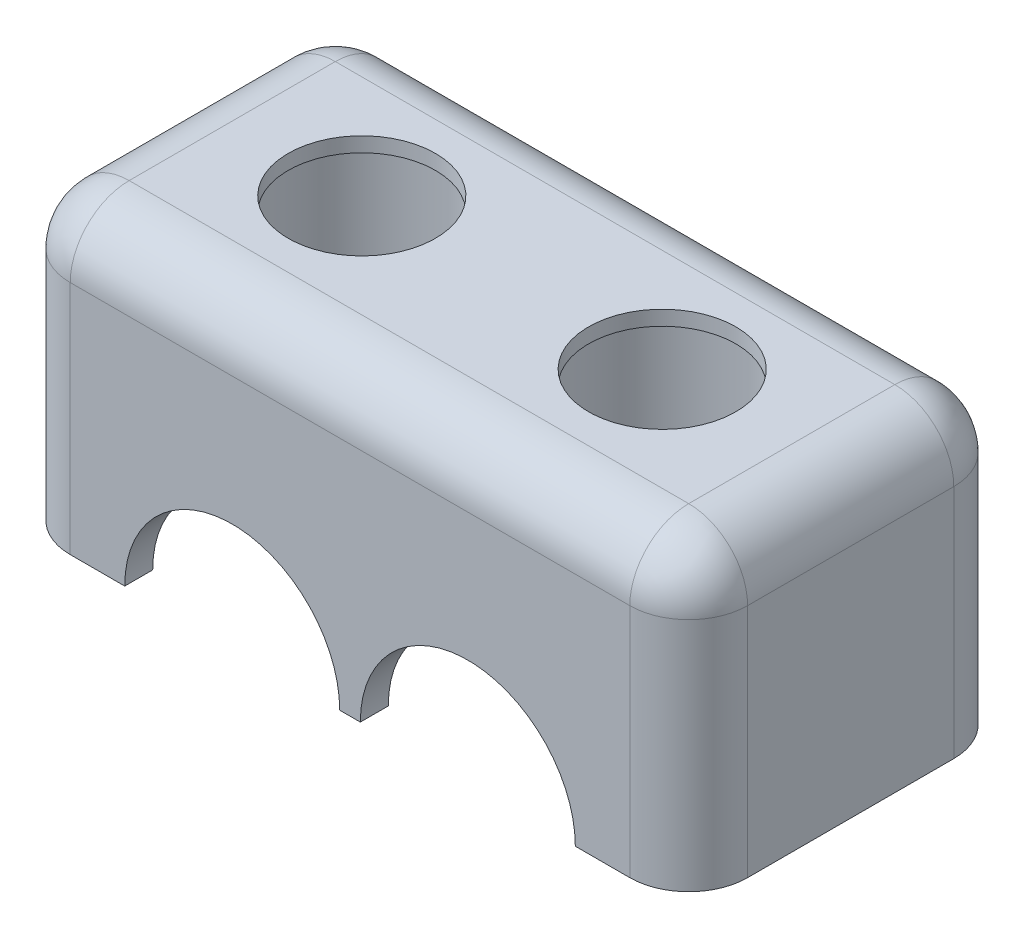
SolidWorks part; units mm, degrees
ref_plane "Front Plane" through (0, 0, 0) normal (0, 0, 1) x (1, 0, 0)
ref_plane "Top Plane" through (0, 0, 0) normal (0, 1, 0) x (1, 0, 0)
ref_plane "Right Plane" through (0, 0, 0) normal (1, 0, 0) x (0, 0, -1)
sketch "Sketch2" plane through (0, 0, 0) normal (0, 0, 1) x (1, 0, 0)
  line L1 (29.21, -5.08) -> (29.21, -25.4)
  line L2 (29.21, -25.4) -> (19.431, -25.4)
  line L3 (0.889, -25.4) -> (-0.889, -25.4)
  line L4 (-19.431, -25.4) -> (-29.21, -25.4)
  line L5 (-29.21, -25.4) -> (-29.21, -5.08)
  line L6 (-24.13, 0) -> (24.13, 0)
  arc A0 (19.431, -25.4) -> (0.889, -25.4) centre (10.16, -25.4) ccw
  arc A1 (-0.889, -25.4) -> (-19.431, -25.4) centre (-10.16, -25.4) ccw
  arc A2 (24.13, 0) -> (29.21, -5.08) centre (24.13, -5.08) cw
  arc A3 (-29.21, -5.08) -> (-24.13, 0) centre (-24.13, -5.08) cw
  point P0 (0, 0)
  point P17 (-29.21, 0)
  dimension "D1" = 18.542
  dimension "D3" = 5.08
  dimension "D2" = 25.4
  dimension "D4" = 19.05
  dimension "D5" = 20.32
extrude "Boss-Extrude1" add sketch "Sketch2" along normal blind 27.94
sketch "Sketch3" plane through (0, -25.4, 0) normal (0, -1, 0) x (1, 0, 0)
  line L0 (-29.21, 27.94) -> (-29.21, 0) construction
  circle A0 centre (-12.954, 13.97) radius 6.35
  circle A1 centre (12.954, 13.97) radius 6.35
  point P4 (0, 0)
  point P8 (-29.21, 13.97)
  point P9 (0, 0)
  dimension "D1" = 12.7
  dimension "D2" = 25.908
  dimension "D3" = 12.954
extrude "Cut-Extrude1" cut sketch "Sketch3" against normal through all both and the other way through all
sketch "Sketch4" plane through (0, -25.4, 0) normal (0, -1, 0) x (1, 0, 0)
  circle A0 centre (-12.954, 13.97) radius 8.001
  circle A1 centre (12.954, 13.97) radius 8.001
  dimension "D1" = 16.002
extrude "Cut-Extrude2" cut sketch "Sketch4" against normal blind 24.13 and the other way through all
sketch "Sketch5" plane through (0, -1.27, 0) normal (0, -1, 0) x (1, 0, 0)
  line L0 (-29.21, 27.94) -> (-29.21, 0) construction
  line L1 (-22.86, 3.683) -> (22.86, 3.683)
  line L2 (-22.86, 3.683) -> (-22.86, 24.257)
  line L3 (-22.86, 24.257) -> (22.86, 24.257)
  line L4 (22.86, 3.683) -> (22.86, 24.257)
  line L5 (-22.86, 3.683) -> (22.86, 24.257) construction
  line L6 (-22.86, 24.257) -> (22.86, 3.683) construction
  point P0 (0, 13.97)
  point P7 (-29.21, 13.97)
  point P8 (-22.86, 13.97)
  point P9 (0, 24.257)
  dimension "D1" = 20.574
  dimension "D2" = 45.72
extrude "Cut-Extrude3" cut sketch "Sketch5" along normal up to surface (11.938 mm away) from offset 12.192 up to face at (-22.9447, -25.4, 13.97)
sketch "Sketch6" plane through (0, -13.462, 0) normal (0, -1, 0) x (1, 0, 0)
  line L0 (22.86, 24.257) -> (-22.86, 24.257) construction
  line L1 (-5.334, 24.257) -> (5.334, 24.257)
  line L2 (-5.334, 24.257) -> (-5.334, 19.685)
  line L3 (-5.334, 19.685) -> (5.334, 19.685)
  line L4 (5.334, 24.257) -> (5.334, 19.685)
  point P6 (0, 24.257)
  dimension "D1" = 4.572
  dimension "D2" = 10.668
extrude "Cut-Extrude4" cut sketch "Sketch6" against normal blind 2.54
ref_plane "Plane1" through (0, 0, 13.97) normal (0, 0, 1) x (1, 0, 0)
mirror "Mirror1" about plane through (0, 0, 13.97) normal (0, 0, 1) of "Cut-Extrude4"
sketch "Sketch7" plane through (0, 0, 0) normal (0, 0, -1) x (-1, 0, 0)
  line L1 (-6.35, -25.4) -> (6.35, -25.4)
  line L2 (-6.35, -25.4) -> (-6.35, -13.462)
  line L3 (-6.35, -13.462) -> (6.35, -13.462)
  line L4 (6.35, -25.4) -> (6.35, -13.462)
  line L5 (22.86, -13.462) -> (5.334, -13.462) construction
  line L7 (0.889, -25.4) -> (-0.889, -25.4) construction
  point P4 (0, -13.462)
  dimension "D1" = 12.7
extrude "Cut-Extrude5" cut sketch "Sketch7" against normal blind 2.54
fillet "Fillet1" radius 5.08 10 edges at (29.21, -15.24, 27.94) (27.7221, -1.4879, 27.94) (-29.21, -15.24, 27.94) (-27.7221, -1.4879, 27.94) (29.21, -15.24, 0) (27.7221, -1.4879, 0) (-27.7221, -1.4879, 0) (0, 0, 27.94) (-29.21, -15.24, 0) (0, 0, 0)
sketch "Sketch8" plane through (0, -13.462, 0) normal (0, -1, 0) x (1, 0, 0)
  line L0 (13.97, 13.97) -> (-13.97, 13.97) construction
  line L9 (-24.13, 2.413) -> (-24.13, 25.527)
  line L10 (-24.13, 25.527) -> (24.13, 25.527)
  line L11 (24.13, 2.413) -> (24.13, 25.527)
  line L12 (-24.13, 2.413) -> (24.13, 2.413)
  point P0 (0, 13.97)
  point P1 (0, 25.527)
  point P2 (0, 0)
  point P4 (24.13, 13.97)
  point P5 (0, 0)
  point P7 (0, 0)
  dimension "D1" = 48.26
  dimension "D2" = 23.114
  dimension "D3" = 24.13
extrude "Cut-Extrude6" cut sketch "Sketch8" along normal blind 12.7 from offset 3.048
